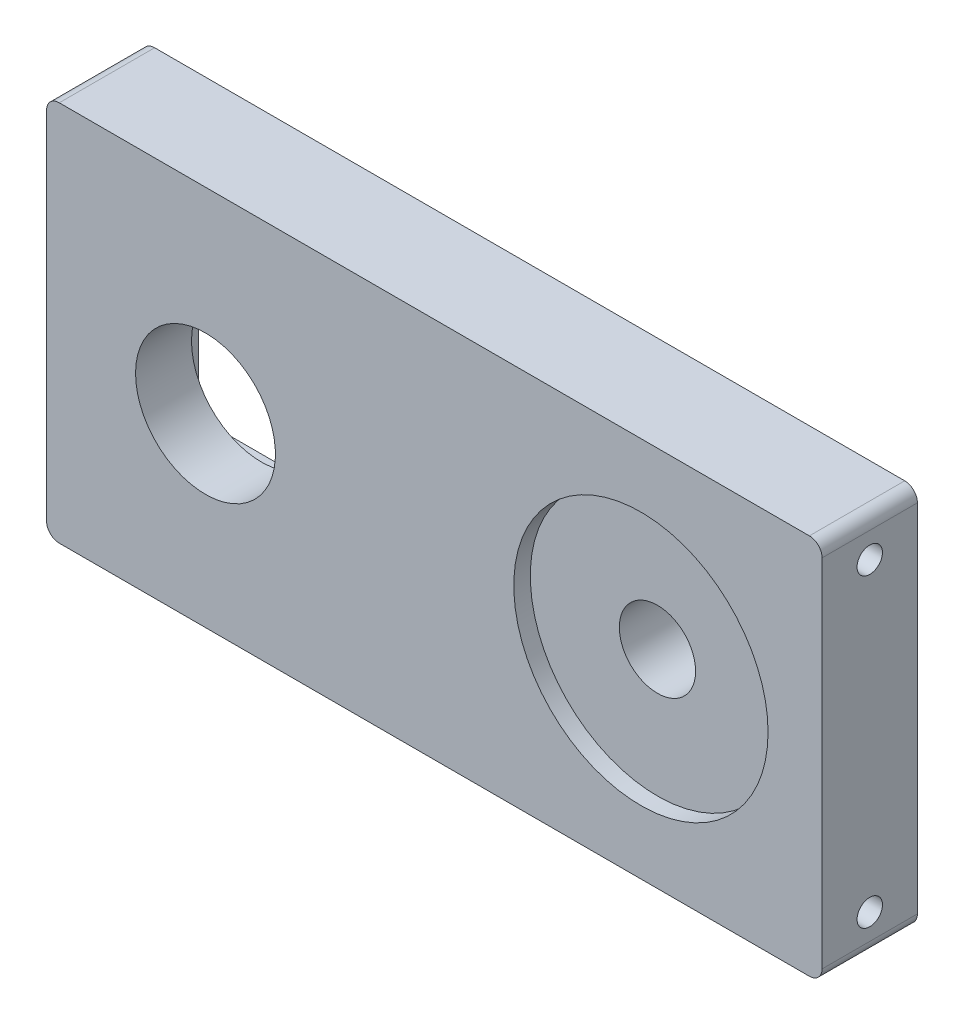
SolidWorks part; units mm, degrees
material "Cedar"
ref_plane "Plan de face" through (0, 0, 0) normal (0, 0, 1) x (1, 0, 0)
ref_plane "Plan de dessus" through (0, 0, 0) normal (0, 1, 0) x (1, 0, 0)
ref_plane "Plan de droite" through (0, 0, 0) normal (1, 0, 0) x (0, 0, -1)
sketch "Sketch1" plane through (0, 0, 0) normal (0, 0, 1) x (1, 0, 0)
  line L1 (-59, 30) -> (59, 30)
  line L2 (-61, 28) -> (-61, -28)
  line L3 (-59, -30) -> (59, -30)
  line L4 (61, 28) -> (61, -28)
  line L5 (-61, 30) -> (61, -30) construction
  line L6 (-61, -30) -> (61, 30) construction
  arc A0 (59, 30) -> (61, 28) centre (59, 28) cw
  arc A1 (59, -30) -> (61, -28) centre (59, -28) ccw
  arc A2 (-61, -28) -> (-59, -30) centre (-59, -28) ccw
  arc A3 (-59, 30) -> (-61, 28) centre (-59, 28) ccw
  point P0 (0, 0)
  dimension "D3" = 2
  dimension "D1" = 122
  dimension "D2" = 60
extrude "Boss-Extrude1" add sketch "Sketch1" along normal mid plane 15
sketch "Sketch2" plane through (61, 0, 0) normal (1, 0, 0) x (0, 0, -1)
  line L0 (0, 0) -> (0, 24) construction
  line L1 (-12.254, 0) -> (18.0308, 0) construction
  circle A0 centre (0, 24) radius 2
  circle A1 centre (0, -24) radius 2
  dimension "D2" = 4
  dimension "D1" = 24
extrude "Cut-Extrude1" cut sketch "Sketch2" against normal blind 15
sketch "Sketch3" plane through (0, 0, -7.5) normal (0, 0, -1) x (-1, 0, 0)
  line L1 (61, 28) -> (61, -28) construction
  circle A0 centre (36, -0.8508) radius 11
  dimension "D1" = 22
  dimension "D2" = 25
extrude "Cut-Extrude3" cut sketch "Sketch3" against normal blind 35 contours A0
sketch "Sketch4" plane through (0, 0, 7.5) normal (0, 0, 1) x (1, 0, 0)
  line L0 (61, -28) -> (61, 28) construction
  circle A0 centre (32.5, 0) radius 6
  dimension "D2" = 12
  dimension "D1" = 28.5
extrude "Cut-Extrude4" cut sketch "Sketch4" against normal blind 19.95
sketch "Sketch6" plane through (0, 0, -7.5) normal (0, 0, -1) x (-1, 0, 0)
  line L0 (49.1, 15.2492) -> (52.1, 12.2492)
  line L1 (22.9, 15.2492) -> (49.1, 15.2492)
  line L2 (19.9, 12.2492) -> (19.9, -13.9508)
  line L3 (22.9, -16.9508) -> (49.1, -16.9508)
  line L4 (52.1, 12.2492) -> (52.1, -13.9508)
  line L5 (19.9, 15.2492) -> (52.1, -16.9508) construction
  line L6 (19.9, -16.9508) -> (52.1, 15.2492) construction
  line L7 (52.1, -13.9508) -> (49.1, -16.9508)
  line L8 (19.9, -13.9508) -> (22.9, -16.9508)
  line L9 (22.9, 15.2492) -> (19.9, 12.2492)
  point P0 (36, -0.8508)
  dimension "D1" = 32.2
extrude "Cut-Extrude5" cut sketch "Sketch6" against normal blind 6.2
sketch "Sketch7" plane through (0, 0, 7.5) normal (0, 0, 1) x (1, 0, 0)
  circle A0 centre (32.5, 0) radius 20
  dimension "D1" = 40
extrude "Cut-Extrude6" cut sketch "Sketch7" against normal blind 2.6
